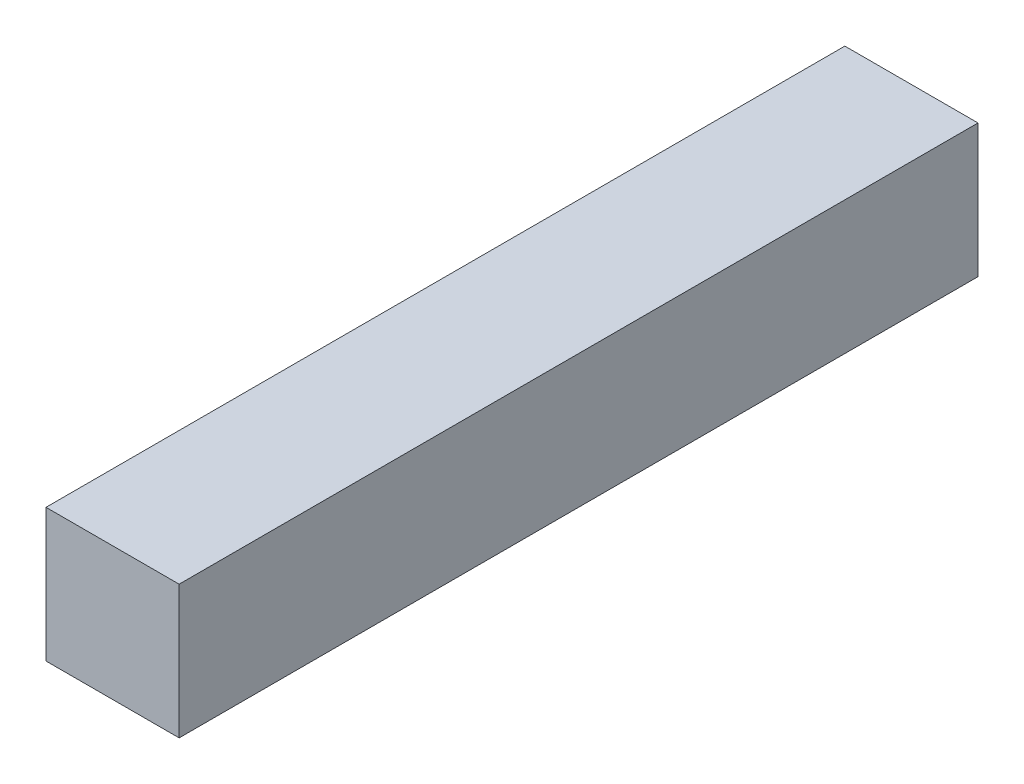
SolidWorks part; units mm, degrees
ref_plane "Front Plane" through (0, 0, 0) normal (0, 0, 1) x (1, 0, 0)
ref_plane "Top Plane" through (0, 0, 0) normal (0, 1, 0) x (1, 0, 0)
ref_plane "Right Plane" through (0, 0, 0) normal (1, 0, 0) x (0, 0, -1)
sketch "Sketch1" plane through (0, 0, 0) normal (0, 0, 1) x (1, 0, 0)
  line L1 (-12.7, -12.7) -> (12.7, -12.7)
  line L2 (-12.7, -12.7) -> (-12.7, 12.7)
  line L3 (-12.7, 12.7) -> (12.7, 12.7)
  line L4 (12.7, -12.7) -> (12.7, 12.7)
  line L5 (-12.7, -12.7) -> (12.7, 12.7) construction
  line L6 (-12.7, 12.7) -> (12.7, -12.7) construction
  point P0 (0, 0)
  dimension "D1" = 25.4
extrude "Boss-Extrude1" add sketch "Sketch1" against normal blind 152.4
